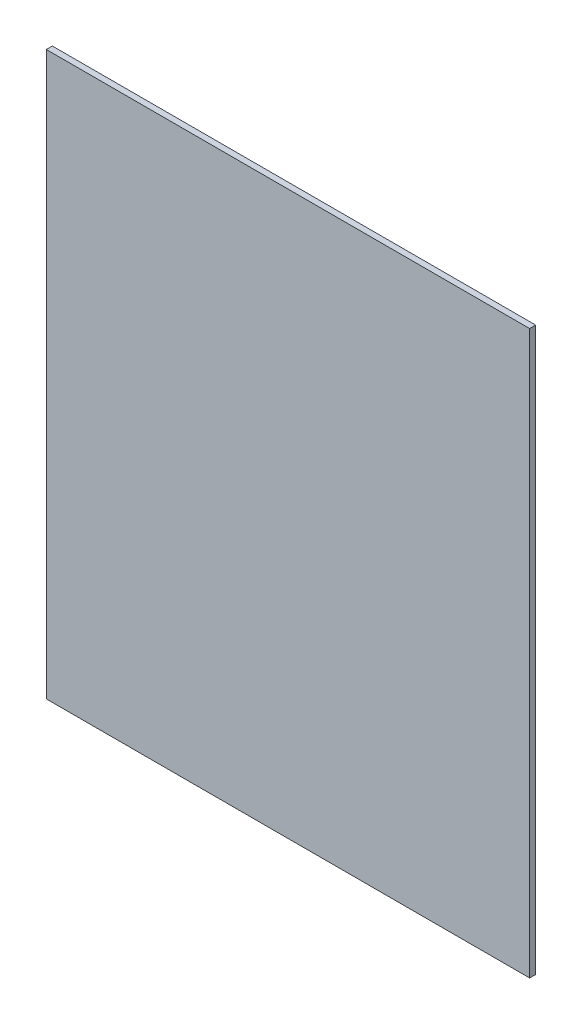
SolidWorks part; units mm, degrees
ref_plane "Front Plane" through (0, 0, 0) normal (0, 0, 1) x (1, 0, 0)
ref_plane "Top Plane" through (0, 0, 0) normal (0, 1, 0) x (1, 0, 0)
ref_plane "Right Plane" through (0, 0, 0) normal (1, 0, 0) x (0, 0, -1)
sketch "Sketch1" plane through (0, 0, 0) normal (0, 0, 1) x (1, 0, 0)
  line L1 (63.5, 73.8886) -> (-63.5, 73.8886)
  line L2 (63.5, 73.8886) -> (63.5, -73.8886)
  line L3 (63.5, -73.8886) -> (-63.5, -73.8886)
  line L4 (-63.5, 73.8886) -> (-63.5, -73.8886)
  line L5 (63.5, 73.8886) -> (-63.5, -73.8886) construction
  line L6 (63.5, -73.8886) -> (-63.5, 73.8886) construction
  point P0 (0, 0)
  dimension "D1" = 127
  dimension "D2" = 147.7772
extrude "Boss-Extrude1" add sketch "Sketch1" along normal blind 1.5875
